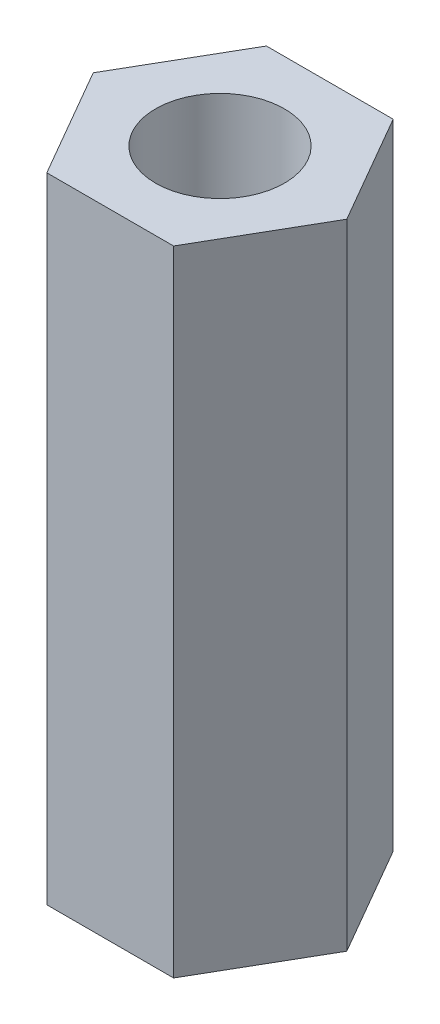
SolidWorks part; units mm, degrees
ref_plane "Front Plane" through (0, 0, 0) normal (0, 0, 1) x (1, 0, 0)
ref_plane "Top Plane" through (0, 0, 0) normal (0, 1, 0) x (1, 0, 0)
ref_plane "Right Plane" through (0, 0, 0) normal (1, 0, 0) x (0, 0, -1)
sketch "Sketch1" plane through (0, 0, 0) normal (0, 1, 0) x (1, 0, 0)
  line L1 (3, 0) -> (1.5, 2.5981)
  line L2 (1.5, 2.5981) -> (-1.5, 2.5981)
  line L3 (-1.5, 2.5981) -> (-3, 0)
  line L4 (-3, 0) -> (-1.5, -2.5981)
  line L5 (-1.5, -2.5981) -> (1.5, -2.5981)
  line L6 (1.5, -2.5981) -> (3, 0)
  circle A0 centre (0, 0) radius 2.5981 construction
  dimension "D1" = 6
extrude "Boss-Extrude1" add sketch "Sketch1" along normal blind 15
sketch "Sketch2" plane through (0, 15, 0) normal (0, 1, 0) x (1, 0, 0)
  circle A0 centre (0, 0) radius 1.525
extrude "Cut-Extrude1" cut sketch "Sketch2" against normal blind 15
